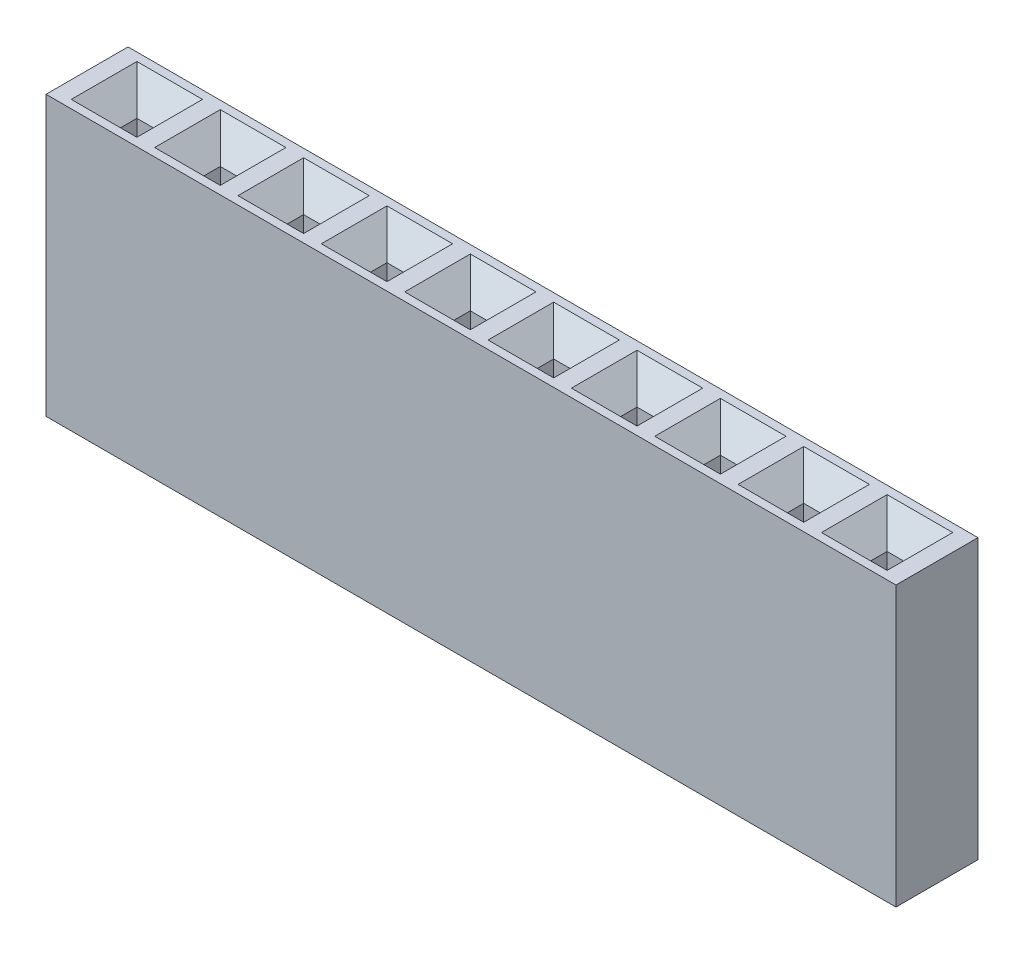
SolidWorks part; units mm, degrees
ref_plane "Спереди" through (0, 0, 0) normal (0, 0, 1) x (1, 0, 0)
ref_plane "Сверху" through (0, 0, 0) normal (0, 1, 0) x (1, 0, 0)
ref_plane "Справа" through (0, 0, 0) normal (1, 0, 0) x (0, 0, -1)
sketch "Эскиз1" plane through (0, 0, 0) normal (0, 1, 0) x (1, 0, 0)
  line L1 (-12.95, 1.25) -> (12.95, 1.25)
  line L2 (-12.95, 1.25) -> (-12.95, -1.25)
  line L3 (-12.95, -1.25) -> (12.95, -1.25)
  line L4 (12.95, 1.25) -> (12.95, -1.25)
  line L5 (-12.95, 1.25) -> (12.95, -1.25) construction
  line L6 (-12.95, -1.25) -> (12.95, 1.25) construction
  point P0 (0, 0)
  dimension "D1" = 2.5
  dimension "D2" = 25.9
extrude "Бобышка-Вытянуть1" add sketch "Эскиз1" along normal blind 8.5
sketch "Эскиз5" plane through (0, 8.5, 0) normal (0, 1, 0) x (1, 0, 0)
  line L0 (-11.43, 0) -> (11.43, 0)
  point P3 (0, 0)
  dimension "D1" = 22.86
sketch "Эскиз2" plane through (0, 8.5, 0) normal (0, 1, 0) x (1, 0, 0)
  line L7 (1.02, 0.25) -> (1.52, 0.25)
  line L8 (1.02, 0.25) -> (1.02, -0.25)
  line L9 (1.02, -0.25) -> (1.52, -0.25)
  line L10 (1.52, 0.25) -> (1.52, -0.25)
  line L11 (1.02, 0.25) -> (1.52, -0.25) construction
  line L12 (1.02, -0.25) -> (1.52, 0.25) construction
  point P5 (1.27, 0)
  point P10 (0, 0)
  point P13 (11.43, 0)
  dimension "D2" = 1.27
  dimension "D3" = 0.5
  dimension "D4" = 11.43
extrude "Вырез-Вытянуть1" cut sketch "Эскиз2" against normal offset from surface (7.5 mm away) 1 up to face at (0, 0, 0)
chamfer "Фаска1" distance 0.75 angle 45 4 edges at (1.02, 8.5, 0) (1.27, 8.5, 0.25) (1.52, 8.5, 0) (1.27, 8.5, -0.25)
sketch "Эскиз6" plane through (0, 8.5, 0) normal (0, 1, 0) x (1, 0, 0)
  line L1 (-1.52, 0.25) -> (-1.02, 0.25)
  line L2 (-1.52, 0.25) -> (-1.52, -0.25)
  line L3 (-1.52, -0.25) -> (-1.02, -0.25)
  line L4 (-1.02, 0.25) -> (-1.02, -0.25)
  line L5 (-1.52, 0.25) -> (-1.02, -0.25) construction
  line L6 (-1.52, -0.25) -> (-1.02, 0.25) construction
  point P0 (-1.27, 0)
  point P5 (0, 0)
  point P10 (0, 0)
  dimension "D1" = 1.27
extrude "Вырез-Вытянуть3" cut sketch "Эскиз6" against normal up to surface (7.5 mm away) up to face at (1.27, 1, 0)
chamfer "Фаска3" distance 0.75 angle 45 4 edges at (-1.02, 8.5, 0) (-1.27, 8.5, 0.25) (-1.52, 8.5, 0) (-1.27, 8.5, -0.25)
sketch "Эскиз4" plane through (12.95, 0, 0) normal (1, 0, 0) x (0, 0, -1)
  line L1 (-0.8, 0) -> (0.8, 0)
  line L2 (-0.8, 0) -> (-0.8, 0.7764)
  line L3 (-0.8, 0.7764) -> (0.8, 0.7764)
  line L4 (0.8, 0) -> (0.8, 0.7764)
  line L5 (-1.25, 0) -> (1.25, 0) construction
  point P6 (0, 0)
  dimension "D1" = 1.6
extrude "Вырез-Вытянуть2" [suppressed] cut sketch "Эскиз4" against normal up to next
sketch "Эскиз3" plane through (0, 0, 0) normal (0, -1, 0) x (1, 0, 0)
  line L0 (-2.79, 0) -> (2.79, 0) construction
  line L3 (0, 0) -> (0, 1.0405) construction
  line L4 (-1.47, 0.2) -> (-1.07, 0.2)
  line L5 (-1.47, 0.2) -> (-1.47, -0.2)
  line L6 (-1.47, -0.2) -> (-1.07, -0.2)
  line L7 (-1.07, 0.2) -> (-1.07, -0.2)
  line L8 (-1.47, 0.2) -> (-1.07, -0.2) construction
  line L9 (-1.47, -0.2) -> (-1.07, 0.2) construction
  line L10 (1.07, 0.2) -> (1.47, 0.2)
  line L11 (1.07, 0.2) -> (1.07, -0.2)
  line L12 (1.07, -0.2) -> (1.47, -0.2)
  line L13 (1.47, 0.2) -> (1.47, -0.2)
  line L14 (1.07, 0.2) -> (1.47, -0.2) construction
  line L15 (1.07, -0.2) -> (1.47, 0.2) construction
  point P3 (1.27, 0)
  point P9 (-1.27, 0)
  dimension "D1" = 2.54
  dimension "D2" = 0.4
extrude "Бобышка-Вытянуть2" [suppressed] add sketch "Эскиз3" along normal blind 3 and the other way up to surface
chamfer "Фаска2" [suppressed] distance 0.3 angle 30
pattern_linear "Линейный массив1" count 5 spacing 2.54 along (-1, 0, 0) of "Вырез-Вытянуть3", "Фаска3"
pattern_linear "Линейный массив2" count 5 spacing 2.54 along (1, 0, 0) of "Фаска1", "Вырез-Вытянуть1"
equation "\"N\"= 10"
equation "\"D2@Эскиз1\"=\"N\"*2.54+0.5"
equation "\"D1@Эскиз5\"=(\"N\"-1)*2.54"
equation "\"D1@Линейный массив1\"=\"N\"/2"
equation "\"D1@Линейный массив2\"=\"N\"/2"
